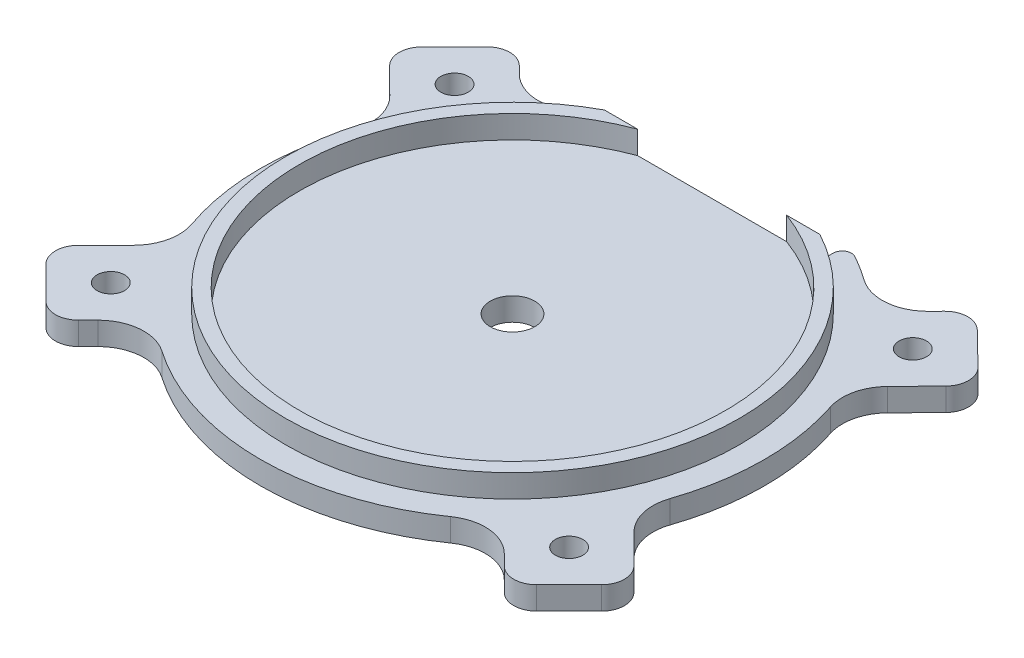
SolidWorks part; units mm, degrees
ref_plane "前视基准面" through (0, 0, 0) normal (0, 0, 1) x (1, 0, 0)
ref_plane "上视基准面" through (0, 0, 0) normal (0, 1, 0) x (1, 0, 0)
ref_plane "右视基准面" through (0, 0, 0) normal (1, 0, 0) x (0, 0, -1)
other "Configuration Table"
sketch "草图1" plane through (0, 0, 0) normal (0, 1, 0) x (1, 0, 0)
  circle A0 centre (0, 0) radius 55
  dimension "D1" = 110
extrude "凸台-拉伸1" add sketch "草图1" along normal blind 5
sketch "草图5" plane through (0, 5, 0) normal (0, 1, 0) x (1, 0, 0)
  line L0 (0, 0) -> (0, 49.5) construction
  line L1 (-23.5, 43.566) -> (23.5, 43.566)
  line L2 (-23.5, 43.566) -> (-23.5, 55.8089)
  line L3 (-23.5, 55.8089) -> (23.5, 55.8089)
  line L4 (23.5, 55.8089) -> (23.5, 43.566)
  dimension "D1" = 47
extrude "切除-拉伸2" cut sketch "草图5" against normal blind 30
fillet "圆角4" radius 2 1 edges at (-23.5, 2.5, -49.7268)
fillet "圆角5" radius 2 1 edges at (23.5, 2.5, -49.7268)
sketch "草图10" plane through (0, 3, 0) normal (0, 1, 0) x (1, 0, 0)
  line L0 (-49.7204, 37.0712) -> (62.5452, 37.0712) construction
  line L1 (-49.7204, 37.0712) -> (-49.7204, -35.3765) construction
  line L2 (-49.7204, -37.9288) -> (73.1761, -37.9288) construction
  circle A0 centre (-49.7204, 37.0712) radius 3
  circle A1 centre (50.2796, 37.0712) radius 3
  circle A2 centre (-49.7204, -37.9288) radius 3
  circle A3 centre (50.2796, -37.9288) radius 3
  dimension "D1" = 6
  dimension "D2" = 6
  dimension "D4" = 6
  dimension "D6" = 6
  dimension "D3" = 100
  dimension "D5" = 75
  dimension "D7" = 100
sketch "草图14" plane through (0, 3, 0) normal (0, 1, 0) x (1, 0, 0)
  line L0 (-49.8986, 23.1329) -> (-63.8625, 37.0448)
  line L1 (-63.8625, 37.0448) -> (-49.7468, 51.2133)
  line L2 (-49.7468, 51.2133) -> (-38.1286, 39.6385)
  line L3 (49.8119, -23.319) -> (64.4217, -37.9288)
  line L4 (-49.6324, -23.6986) -> (-63.8626, -37.9288)
  line L5 (-63.8626, -37.9288) -> (-49.7204, -52.0709)
  line L6 (-49.7204, -52.0709) -> (-37.6979, -40.0484)
  line L7 (38.4757, 39.3016) -> (50.1189, 51.2124)
  line L8 (50.1189, 51.2124) -> (64.4208, 37.2319)
  line L9 (64.4208, 37.2319) -> (50.1345, 22.6171)
  line L10 (64.4217, -37.9288) -> (50.2796, -52.0709)
  line L11 (50.2796, -52.0709) -> (37.9849, -39.7762)
  arc A0 (-26.4623, 48.2156) -> (26.4623, 48.2156) centre (0, 0) ccw construction
  arc A1 (-49.6324, -23.6986) -> (-37.6979, -40.0484) centre (0, 0) ccw
  arc A2 (-49.8986, 23.1329) -> (-38.1286, 39.6385) centre (0, 0) cw
  arc A3 (38.4757, 39.3016) -> (50.1345, 22.6171) centre (0, 0) cw
  arc A4 (49.8119, -23.319) -> (37.9849, -39.7762) centre (0, 0) cw
  dimension "D1" = 10
  dimension "D2" = 10
  dimension "D3" = 10
  dimension "D4" = 10
  dimension "D5" = 10
  dimension "D6" = 10
  dimension "D7" = 10
  dimension "D8" = 10
  dimension "D9" = 10
  dimension "D10" = 10
  dimension "D11" = 10
  dimension "D12" = 10
extrude "凸台-拉伸3" add sketch "草图14" against normal up to surface and the other way up to surface up to face at (0, 0, -29.1602) other way up to face at (0, 5, -29.1602)
fillet "圆角7" radius 10 8 edges at (-49.6324, 2.5, 23.6986) (-37.6979, 2.5, 40.0484) (37.9849, 2.5, 39.7762) (49.8119, 2.5, 23.319) (50.1345, 2.5, -22.6171) (38.4757, 2.5, -39.3016) (-38.1286, 2.5, -39.6385) (-49.8986, 2.5, -23.1329)
fillet "圆角8" radius 5 8 edges at (-49.7468, 2.5, -51.2133) (-63.8625, 2.5, -37.0448) (-63.8626, 2.5, 37.9288) (-49.7204, 2.5, 52.0709) (50.2796, 2.5, 52.0709) (64.4217, 2.5, 37.9288) (64.4208, 2.5, -37.2319) (50.1189, 2.5, -51.2124)
extrude "切除-拉伸5" cut sketch "草图10" against normal mid plane 10
sketch "草图15" plane through (0, 5, 0) normal (0, 1, 0) x (1, 0, 0)
  circle A0 centre (0, 0) radius 4.85
  dimension "D1" = 9.7
extrude "切除-拉伸6" cut sketch "草图15" against normal blind 10
sketch "草图17" plane through (0, 5, 0) normal (0, 1, 0) x (1, 0, 0)
  line L0 (-23.5, 43.566) -> (23.5, 43.566) construction
  line L1 (-23.5, 43.566) -> (-16.2558, 43.566)
  line L2 (16.2558, 43.566) -> (23.5, 43.566)
  arc A0 (23.5, 43.566) -> (-23.5, 43.566) centre (0, 0) cw
  arc A1 (-16.2558, 43.566) -> (16.2558, 43.566) centre (0, 0) ccw
extrude "凸台-拉伸4" add sketch "草图17" along normal blind 5
